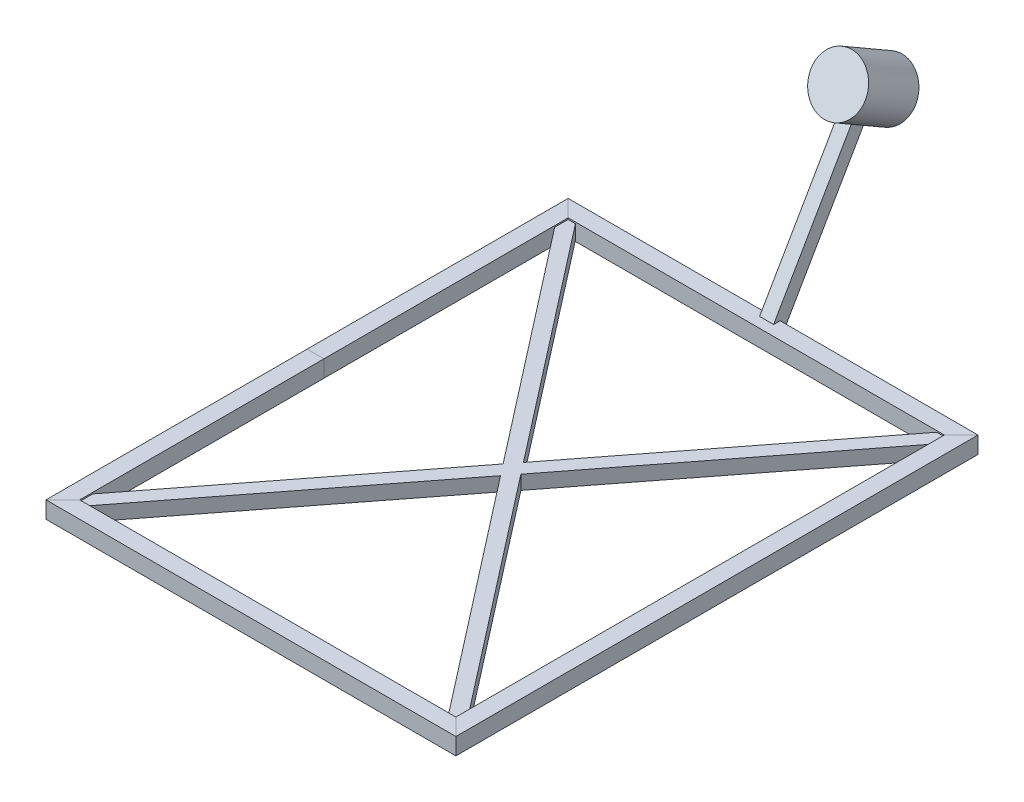
SolidWorks part; units mm, degrees
ref_plane "Front Plane" through (0, 0, 0) normal (0, 0, 1) x (1, 0, 0)
ref_plane "Top Plane" through (0, 0, 0) normal (0, 1, 0) x (1, 0, 0)
ref_plane "Right Plane" through (0, 0, 0) normal (1, 0, 0) x (0, 0, -1)
sketch "Sketch1" plane through (0, 0, 0) normal (0, 0, 1) x (1, 0, 0)
  line L0 (0, 0) -> (-374.8726, 0) construction
  line L1 (-342.9, -12.7) -> (-368.3, -12.7)
  line L2 (-342.9, -12.7) -> (-342.9, 12.7)
  line L3 (-342.9, 12.7) -> (-368.3, 12.7)
  line L4 (-368.3, -12.7) -> (-368.3, 12.7)
  line L5 (-342.9, -12.7) -> (-368.3, 12.7) construction
  line L6 (-342.9, 12.7) -> (-368.3, -12.7) construction
  line L7 (-340.36, 15.24) -> (-370.84, 15.24)
  line L8 (-370.84, -15.24) -> (-370.84, 15.24)
  line L9 (-340.36, -15.24) -> (-370.84, -15.24)
  line L10 (-340.36, -15.24) -> (-340.36, 15.24)
  point P0 (-355.6, 0)
  point P5 (0, 0)
  dimension "D1" = 25.4
  dimension "D2" = 25.4
  dimension "D3" = 355.6
  dimension "D4" = 374.8726
  dimension "D5" = 2.54
sketch "Sketch3" plane through (0, 0, 0) normal (0, 1, 0) x (1, 0, 0)
  line L1 (355.6, -457.2) -> (-355.6, -457.2)
  line L2 (355.6, -457.2) -> (355.6, 457.2)
  line L3 (355.6, 457.2) -> (-355.6, 457.2)
  line L4 (-355.6, -457.2) -> (-355.6, 457.2)
  line L5 (355.6, -457.2) -> (-355.6, 457.2) construction
  line L6 (355.6, 457.2) -> (-355.6, -457.2) construction
  point P0 (0, 0)
  dimension "D1" = 914.4
  dimension "D2" = 711.2
sweep "Sweep1" add profiles "Sketch1" path "Sketch3"
sketch "Sketch4" plane through (0, 0, 0) normal (0, 1, 0) x (1, 0, 0)
  line L0 (-370.84, 456.8617) -> (350.7782, -472.44)
  line L1 (-370.84, 456.8617) -> (-350.7782, 472.44)
  line L2 (350.7782, -472.44) -> (370.84, -456.8617)
  line L3 (-350.7782, 472.44) -> (370.84, -456.8617)
  line L4 (-370.84, 456.8617) -> (370.84, -456.8617) construction
  line L5 (350.7782, -472.44) -> (-350.7782, 472.44) construction
  line L6 (0, 0) -> (194.9872, 0)
  line L9 (370.84, 472.44) -> (370.84, -472.44) construction
  line L10 (370.84, -472.44) -> (-370.84, -472.44) construction
  line L11 (-368.3, -454.3374) -> (348.226, 469.9)
  line L12 (-368.3, -454.3374) -> (-348.226, -469.9)
  line L13 (348.226, 469.9) -> (368.3, 454.3374)
  line L14 (-348.226, -469.9) -> (368.3, 454.3374)
  line L15 (-368.3, -454.3374) -> (368.3, 454.3374) construction
  line L16 (348.226, 469.9) -> (-348.226, -469.9) construction
  line L17 (368.3, 469.9) -> (368.3, -469.9) construction
  line L18 (-368.3, 469.9) -> (368.3, 469.9) construction
  point P1 (0, 0)
  point P3 (0, 0)
  point P19 (0, 0)
  dimension "D1" = 25.4
  dimension "D2" = 25.4
extrude "Boss-Extrude3" add sketch "Sketch4" along normal blind 12.7 and the other way blind 12.7 separate body contours L3 L2 L0 L1 | L11 L12 L14 L13
sketch "Sketch5" plane through (0, 0, 0) normal (1, 0, 0) x (0, 0, -1)
  line L0 (624.84, 248.7245) -> (472.44, -15.24)
  line L1 (624.84, 248.7245) -> (602.843, 261.4245)
  line L2 (472.44, -15.24) -> (450.443, -2.54)
  line L3 (602.843, 261.4245) -> (450.443, -2.54)
  line L4 (624.84, 248.7245) -> (450.443, -2.54) construction
  line L5 (472.44, -15.24) -> (602.843, 261.4245) construction
  line L6 (472.44, -15.24) -> (-472.44, -15.24) construction
  point P0 (0, 0)
  point P1 (537.6415, 123.0923)
  dimension "D1" = 25.4
  dimension "D2" = 30
  dimension "D3" = 304.8
extrude "Boss-Extrude13" add sketch "Sketch5" along normal blind 12.7 and the other way blind 12.7 separate body contours L3 L2 L0 L1
sketch "Sketch7" plane through (0, -208.3825, -360.9291) normal (0, -0.5, -0.866) x (-1, 0, 0)
  circle A0 centre (0, 572.4735) radius 49.2948
extrude "Boss-Extrude14" add sketch "Sketch7" along normal blind 39.37 and the other way blind 65.786 separate body contours A0
equation "\"tube_size\"= 1in"
equation "\"D1@Sketch1\"=\"tube_size\""
equation "\"D2@Sketch1\"=\"tube_size\""
equation "\"tube_thickness\"= - 0.1"
equation "\"D5@Sketch1\"=\"tube_thickness\""
equation "\"frame_w\"= 28"
equation "\"frame_l\" = 36in"
equation "\"headtube_angle\"=32.0262"
equation "\"tub\"=1"
